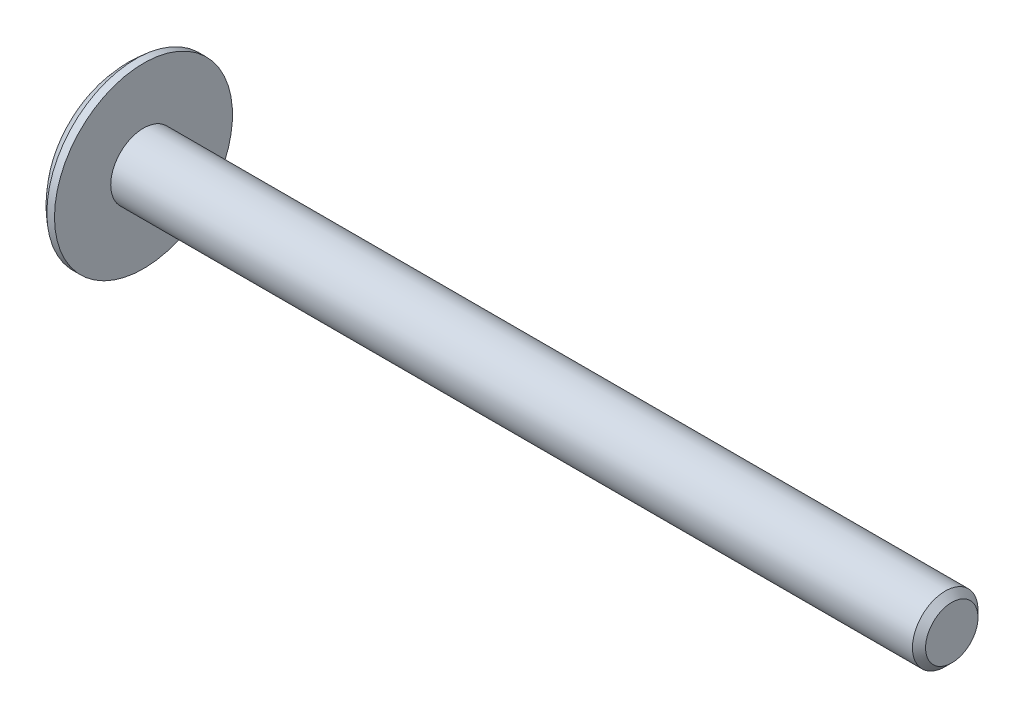
SolidWorks part; units mm, degrees
ref_plane "Front Plane" through (0, 0, 0) normal (0, 0, 1) x (1, 0, 0)
ref_plane "Top Plane" through (0, 0, 0) normal (0, 1, 0) x (1, 0, 0)
ref_plane "Right Plane" through (0, 0, 0) normal (1, 0, 0) x (0, 0, -1)
sketch "Sketch1" plane through (0, 0, 0) normal (0, 0, 1) x (1, 0, 0)
  line L0 (0, 0) -> (13362.5599, 0) construction
  line L1 (0, 0) -> (0, -13362.5599) construction
  line L2 (0, 0) -> (0, 1.425)
  line L3 (1.3, 4.0745) -> (1.65, 4.0745)
  line L4 (1.65, 4.0745) -> (1.65, 1.5)
  line L5 (1.65, 1.5) -> (38.35, 1.5)
  line L6 (38.35, 1.5) -> (38.65, 1.2)
  line L7 (38.65, 1.2) -> (38.65, 0)
  line L8 (0, 0) -> (38.65, 0)
  arc A0 (0, 1.425) -> (1.3, 4.0745) centre (3.35, 1.425) cw
  dimension "D1" = 3.35
  dimension "D2" = 1.425
  dimension "D3" = 1.65
  dimension "D4" = 0.35
  dimension "D5" = 36.7
  dimension "D6" = 0.3
  dimension "D7" = 3
  dimension "D8" = 45
revolve "Revolve1" add sketch "Sketch1" angle 360 about L8
sketch "Sketch2" plane through (0, 0, 0) normal (-1, 0, 0) x (0, 0, 1)
  line L1 (0, 1.1547) -> (-1, 0.5774)
  line L2 (-1, 0.5774) -> (-1, -0.5774)
  line L3 (-1, -0.5774) -> (0, -1.1547)
  line L4 (0, -1.1547) -> (1, -0.5774)
  line L5 (1, -0.5774) -> (1, 0.5774)
  line L6 (1, 0.5774) -> (0, 1.1547)
  circle A0 centre (0, 0) radius 1 construction
  point P1 (0, 0)
  dimension "D1" = 2
extrude "Cut-Extrude1" cut sketch "Sketch2" against normal blind 1
